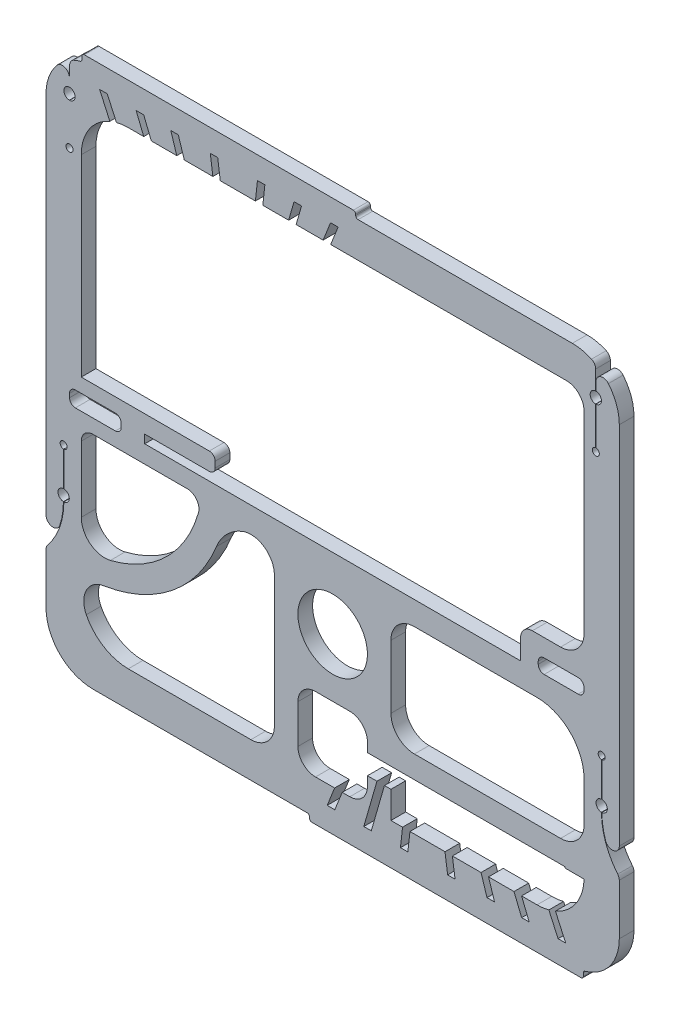
SolidWorks part; units mm, degrees
ref_plane "Front Plane" through (0, 0, 0) normal (0, 0, 1) x (1, 0, 0)
ref_plane "Top Plane" through (0, 0, 0) normal (0, 1, 0) x (1, 0, 0)
ref_plane "Right Plane" through (0, 0, 0) normal (1, 0, 0) x (0, 0, -1)
sketch "Sketch1" plane through (0, 0, 0) normal (0, 0, 1) x (1, 0, 0)
  line L0 (44.642, 21.8842) -> (44.642, 18.0742) construction
  line L1 (-10.1934, 21.8842) -> (51.7832, 21.8842)
  line L2 (-10.1934, 21.8842) -> (-10.1934, -36.406)
  line L3 (-10.1934, -36.406) -> (51.7832, -36.406)
  line L4 (51.7832, 21.8842) -> (51.7832, -36.406)
  line L5 (47.9732, -32.596) -> (-6.3834, -32.596)
  line L6 (47.9732, -32.596) -> (47.9732, 18.0742)
  line L7 (47.9732, 18.0742) -> (-6.3834, 18.0742)
  line L8 (-6.3834, -32.596) -> (-6.3834, 18.0742)
  line L9 (44.642, 19.9792) -> (-35.1587, 19.9792) construction
  line L10 (-6.3834, -31.0517) -> (-10.1934, -31.0517) construction
  line L11 (-8.2884, -31.0517) -> (-8.2884, 6.9585) construction
  line L12 (20.6521, 19.9792) -> (21.1982, 19.9792) construction
  line L14 (3.0779, -32.596) -> (3.0779, -36.406) construction
  line L15 (3.0779, -34.501) -> (37.3423, -34.501) construction
  line L16 (47.9732, -11.8991) -> (47.9732, 12.9942) construction
  line L17 (51.7832, 15.2205) -> (47.9732, 15.2205) construction
  line L18 (49.8782, 15.2205) -> (49.8782, -0.9437) construction
  line L20 (20.9378, -34.501) -> (20.3916, -34.501) construction
  line L21 (-6.3834, 8.0412) -> (-6.3834, -11.8991) construction
  dimension "D1" = 3.81
  dimension "D2" = 3.81
extrude "Boss-Extrude1" add sketch "Sketch1" along normal blind 1.5875
sketch "Sketch2" plane through (0, 0, 0) normal (0, 0, -1) x (-1, 0, 0)
  line L0 (-47.9732, -32.596) -> (-47.9732, 18.0742) construction
  line L1 (-34.8696, 3.2518) -> (6.3834, 3.2518) construction
  line L2 (-47.9732, 3.653) -> (-47.9732, 0.4065) construction
  line L3 (-37.4096, 0.7118) -> (6.3834, 0.7118) construction
  line L4 (6.3834, 3.2518) -> (6.3834, 0.7118) construction
  line L5 (6.3834, 18.0742) -> (6.3834, -32.596) construction
  line L8 (-47.9732, -13.182) -> (-9.1041, -13.182)
  line L9 (-47.9732, -13.182) -> (-47.9732, -10.642)
  line L10 (-47.9732, -10.642) -> (-6.771, -10.642)
  line L11 (1.357, -21.2563) -> (14.2432, -21.2563) construction
  line L12 (6.3834, -23.7963) -> (6.3834, -26.3363)
  line L13 (-47.9732, 13.8154) -> (-47.9732, 11.2754) construction
  line L14 (-41.1149, -10.642) -> (-0.4749, -10.642) construction
  line L15 (-40.2005, -1.1932) -> (-39.5655, -1.1932) construction
  arc A0 (-47.9732, 11.2754) -> (-37.4096, 0.7118) centre (-47.9732, 0.7118) cw construction
  arc A1 (-47.9732, 13.8154) -> (-34.8696, 3.2518) centre (-47.9732, 0.4065) cw construction
  arc A2 (6.3834, -23.7963) -> (-6.771, -10.642) centre (6.3834, -10.642) cw
  arc A3 (-9.1041, -13.182) -> (6.3834, -26.3363) centre (6.3834, -10.642) ccw
  circle A5 centre (1.357, -18.2591) radius 2.9972 construction
  line M5 (-47.9732, -32.596) -> (-47.9732, 18.0742)
  line M7 (6.3834, 18.0742) -> (6.3834, -32.596)
  dimension "D5" = 2.54
  dimension "D1" = 2.54
  dimension "D2" = 2.54
  dimension "D3" = 2.54
  dimension "D4" = 2.54
  dimension "D6" = 2.54
  dimension "D7" = 2.54
  dimension "D8" = 1.905
extrude "Boss-Extrude2" add sketch "Sketch2" against normal up to surface (1.5875 mm away) contours L8 A3 A2 L10 M7 M5 up to face at (20.7949, -7.2609, 1.5875)
sketch "Sketch3" plane through (0, 0, 0) normal (0, 0, -1) x (-1, 0, 0)
  line L0 (-47.9732, -7.1876) -> (-41.1149, -7.1876)
  line L1 (-47.9732, -10.642) -> (-47.9732, 18.0742) construction
  line L2 (-47.9732, -10.642) -> (-6.771, -10.642) construction
  line L3 (-41.1149, -7.1876) -> (-41.1149, -10.642)
  line L5 (-41.1149, -10.642) -> (-43.0199, -10.642)
  line L6 (-43.0199, -10.642) -> (-43.0199, -9.0926)
  line L7 (-43.0199, -9.0926) -> (-47.9732, -9.0926)
  line L8 (-47.9732, -9.0926) -> (-47.9732, -7.1876)
  line L19 (-0.4749, -9.7276) -> (-41.1149, -9.7276) construction
  line L21 (-41.1149, -9.7276) -> (-41.1149, -10.642) construction
  dimension "D1" = 1.905
  dimension "D2" = 1.905
  dimension "D3" = 2.54
extrude "Boss-Extrude3" add sketch "Sketch3" against normal up to surface (1.5875 mm away) up to face at (18.535, -2.3312, 1.5875)
fillet "Fillet1" radius 5.08 4 edges at (51.7832, -36.406, 0.7937) (-10.1934, -36.406, 0.7937) (-10.1934, 21.8842, 0.7937) (51.7832, 21.8842, 0.7937)
fillet "Fillet2" radius 5.08 6 edges at (9.1041, -13.182, 0.7937) (47.9732, -13.182, 0.7937) (47.9732, -32.596, 0.7937) (-6.3834, -32.596, 0.7937) (-6.3834, 18.0742, 0.7937) (6.771, -10.642, 0.7937)
fillet "Fillet3" radius 2.54 3 edges at (47.9732, -7.1876, 0.7938) (-6.3834, -26.3363, 0.7937) (-6.3834, -23.7963, 0.7937)
sketch "Sketch5" plane through (0, 0, 0) normal (0, 0, -1) x (-1, 0, 0)
  line L1 (-27.0941, -13.182) -> (-14.4957, -13.182)
  line L2 (-27.0941, -13.182) -> (-27.0941, -32.596)
  line L3 (-27.0941, -32.596) -> (-14.4957, -32.596)
  line L4 (-14.4957, -13.182) -> (-14.4957, -32.596)
  line L5 (1.3034, -32.596) -> (-42.8932, -32.596) construction
  line L6 (-24.5541, -18.2972) -> (-27.0941, -18.2972) construction
  line L7 (-42.8932, -13.182) -> (-12.943, -13.182) construction
  line L9 (-17.0357, -18.2972) -> (-14.4957, -18.2972) construction
  circle A1 centre (-20.7949, -18.2972) radius 3.7592 construction
  dimension "D1" = 2.54
extrude "Boss-Extrude4" add sketch "Sketch5" against normal up to surface (1.5875 mm away) up to face at (45.4966, -9.8673, 1.5875)
sketch "Sketch6" plane through (0, 0, 0) normal (0, 0, -1) x (-1, 0, 0)
  circle A0 centre (-20.7949, -18.2972) radius 3.7592 construction
  circle A1 centre (-20.7949, -18.2972) radius 3.7592
extrude "Cut-Extrude2" cut sketch "Sketch6" against normal up to surface (1.5875 mm away) up to face at (5.503, -23.566, 1.5875)
sketch "Sketch7" plane through (0, 0, 0) normal (0, 0, -1) x (-1, 0, 0)
  line L0 (-27.0941, -13.182) -> (-27.0941, -32.596) construction
  line L1 (-24.5541, -24.5964) -> (-17.0357, -24.5964)
  line L2 (-24.5541, -24.5964) -> (-24.5541, -32.596)
  line L3 (-24.5541, -32.596) -> (-17.0357, -32.596)
  line L4 (-17.0357, -24.5964) -> (-17.0357, -32.596)
  line L5 (-14.4957, -32.596) -> (-14.4957, -13.182) construction
  line L6 (1.3034, -32.596) -> (-14.4957, -32.596) construction
  line L7 (-20.7949, -22.0564) -> (-6.5424, -22.0564) construction
  line L8 (-20.7949, -22.0564) -> (-20.7949, -21.3452) construction
  circle A0 centre (-20.7949, -18.2972) radius 3.7592 construction
  dimension "D1" = 2.54
  dimension "D2" = 2.54
  dimension "D3" = 2.54
extrude "Cut-Extrude3" cut sketch "Sketch7" against normal up to surface (1.5875 mm away) up to face at (24.5541, -18.2972, 1.5875)
fillet "Fillet5" radius 1.905 4 edges at (24.5541, -32.596, 0.7937) (17.0357, -32.596, 0.7938) (17.0357, -24.5964, 0.7938) (24.5541, -24.5964, 0.7938)
sketch "Sketch8" plane through (0, 0, 0) normal (0, 0, -1) x (-1, 0, 0)
  line L0 (-47.9732, -27.516) -> (-47.9732, -18.262) construction
  line L1 (-47.9732, -25.103) -> (-27.0941, -25.103)
  line L2 (-47.9732, -25.103) -> (-47.9732, -27.643)
  line L3 (-47.9732, -27.643) -> (-27.0941, -27.643)
  line L4 (-27.0941, -25.103) -> (-27.0941, -27.643)
  line L5 (-27.0941, -13.182) -> (-27.0941, -32.596) construction
  line L6 (-45.7916, -27.643) -> (-20.3916, -27.643) construction
  dimension "D1" = 2.54
extrude "Boss-Extrude5" add sketch "Sketch8" against normal up to surface (1.5875 mm away) up to face at (20.7949, -28.5962, 1.5875)
fillet "Fillet6" radius 2.54 5 edges at (27.0941, -13.182, 0.7937) (14.4957, -13.182, 0.7937) (14.4957, -32.596, 0.7937) (27.0941, -25.103, 0.7937) (47.9732, -25.103, 0.7937)
sketch "Sketch4" plane through (0, 0, 0) normal (0, 0, -1) x (-1, 0, 0)
  line L32 (4.2018, 13.1212) -> (4.2018, 15.0262)
  line L33 (4.2018, 15.0262) -> (1.9539, 15.0262)
  line L34 (1.9539, 15.0262) -> (4.2018, 19.9792)
  line L35 (4.2018, 19.9792) -> (3.6556, 19.9792)
  line L36 (3.6556, 19.9792) -> (1.4078, 15.0262)
  line L37 (1.4078, 15.0262) -> (-1.7417, 15.0262)
  line L38 (-1.7417, 15.0262) -> (0.2648, 19.9792)
  line L39 (0.2648, 19.9792) -> (-0.2814, 19.9792)
  line L40 (-0.2814, 19.9792) -> (-2.2879, 15.0262)
  line L41 (-2.2879, 15.0262) -> (-5.0437, 15.0262)
  line L42 (-5.0437, 15.0262) -> (-3.469, 19.9792)
  line L43 (-3.469, 19.9792) -> (-4.0152, 19.9792)
  line L44 (-4.0152, 19.9792) -> (-5.5899, 15.0262)
  line L45 (-5.5899, 15.0262) -> (-8.3965, 15.0262)
  line L46 (-8.3965, 15.0262) -> (-7.7108, 19.9792)
  line L47 (-7.7108, 19.9792) -> (-8.257, 19.9792)
  line L48 (-8.257, 19.9792) -> (-8.9427, 15.0262)
  line L49 (-8.9427, 15.0262) -> (-12.2319, 15.0262)
  line L50 (-12.2319, 15.0262) -> (-12.7781, 19.9792)
  line L51 (-12.7781, 19.9792) -> (-13.3242, 19.9792)
  line L52 (-13.3242, 19.9792) -> (-12.7781, 15.0262)
  line L53 (-12.7781, 15.0262) -> (-15.2926, 15.0262)
  line L54 (-15.2926, 15.0262) -> (-16.7151, 19.9792)
  line L55 (-16.7151, 19.9792) -> (-17.2612, 19.9792)
  line L56 (-17.2612, 19.9792) -> (-15.8388, 15.0262)
  line L57 (-15.8388, 15.0262) -> (-18.6963, 15.0262)
  line L58 (-18.6963, 15.0262) -> (-20.6521, 19.9792)
  line L59 (-20.6521, 19.9792) -> (-21.1982, 19.9792)
  line L60 (-21.1982, 19.9792) -> (-19.2425, 15.0262)
  line L61 (-19.2425, 15.0262) -> (-21.1982, 15.0262)
  line L62 (-21.1982, 15.0262) -> (-21.1982, 13.1212)
  line L63 (-21.1982, 13.1212) -> (4.2018, 13.1212)
  line L64 (4.2018, 13.1212) -> (4.2018, 15.0262) construction
  line L65 (4.2018, 15.0262) -> (1.9539, 15.0262) construction
  line L66 (1.9539, 15.0262) -> (4.2018, 19.9792) construction
  line L67 (4.2018, 19.9792) -> (3.6556, 19.9792) construction
  line L68 (3.6556, 19.9792) -> (1.4078, 15.0262) construction
  line L69 (1.4078, 15.0262) -> (-1.7417, 15.0262) construction
  line L70 (-1.7417, 15.0262) -> (0.2648, 19.9792) construction
  line L71 (0.2648, 19.9792) -> (-0.2814, 19.9792) construction
  line L72 (-0.2814, 19.9792) -> (-2.2879, 15.0262) construction
  line L73 (-2.2879, 15.0262) -> (-5.0437, 15.0262) construction
  line L74 (-5.0437, 15.0262) -> (-3.469, 19.9792) construction
  line L75 (-3.469, 19.9792) -> (-4.0152, 19.9792) construction
  line L76 (-4.0152, 19.9792) -> (-5.5899, 15.0262) construction
  line L77 (-5.5899, 15.0262) -> (-8.3965, 15.0262) construction
  line L78 (-8.3965, 15.0262) -> (-7.7108, 19.9792) construction
  line L79 (-7.7108, 19.9792) -> (-8.257, 19.9792) construction
  line L80 (-8.257, 19.9792) -> (-8.9427, 15.0262) construction
  line L81 (-8.9427, 15.0262) -> (-12.2319, 15.0262) construction
  line L82 (-12.2319, 15.0262) -> (-12.7781, 19.9792) construction
  line L83 (-12.7781, 19.9792) -> (-13.3242, 19.9792) construction
  line L84 (-13.3242, 19.9792) -> (-12.7781, 15.0262) construction
  line L85 (-12.7781, 15.0262) -> (-15.2926, 15.0262) construction
  line L86 (-15.2926, 15.0262) -> (-16.7151, 19.9792) construction
  line L87 (-16.7151, 19.9792) -> (-17.2612, 19.9792) construction
  line L88 (-17.2612, 19.9792) -> (-15.8388, 15.0262) construction
  line L89 (-15.8388, 15.0262) -> (-18.6963, 15.0262) construction
  line L90 (-18.6963, 15.0262) -> (-20.6521, 19.9792) construction
  line L91 (-20.6521, 19.9792) -> (-21.1982, 19.9792) construction
  line L92 (-21.1982, 19.9792) -> (-19.2425, 15.0262) construction
  line L93 (-19.2425, 15.0262) -> (-21.1982, 15.0262) construction
  line L94 (-21.1982, 15.0262) -> (-21.1982, 13.1212) construction
  line L95 (-21.1982, 13.1212) -> (4.2018, 13.1212) construction
  line L96 (-45.7916, -27.643) -> (-45.7916, -29.548)
  line L97 (-45.7916, -29.548) -> (-43.5438, -29.548)
  line L98 (-43.5438, -29.548) -> (-45.7916, -34.501)
  line L99 (-45.7916, -34.501) -> (-45.2455, -34.501)
  line L100 (-45.2455, -34.501) -> (-42.9976, -29.548)
  line L101 (-42.9976, -29.548) -> (-39.8482, -29.548)
  line L102 (-39.8482, -29.548) -> (-41.8546, -34.501)
  line L103 (-41.8546, -34.501) -> (-41.3085, -34.501)
  line L104 (-41.3085, -34.501) -> (-39.302, -29.548)
  line L105 (-39.302, -29.548) -> (-36.5462, -29.548)
  line L106 (-36.5462, -29.548) -> (-38.1208, -34.501)
  line L107 (-38.1208, -34.501) -> (-37.5747, -34.501)
  line L108 (-37.5747, -34.501) -> (-36, -29.548)
  line L109 (-36, -29.548) -> (-33.1934, -29.548)
  line L110 (-33.1934, -29.548) -> (-33.879, -34.501)
  line L111 (-33.879, -34.501) -> (-33.3329, -34.501)
  line L112 (-33.3329, -34.501) -> (-32.6472, -29.548)
  line L113 (-32.6472, -29.548) -> (-29.358, -29.548)
  line L114 (-29.358, -29.548) -> (-28.8118, -34.501)
  line L115 (-28.8118, -34.501) -> (-28.2656, -34.501)
  line L116 (-28.2656, -34.501) -> (-28.8118, -29.548)
  line L117 (-28.8118, -29.548) -> (-26.2973, -29.548)
  line L118 (-26.2973, -29.548) -> (-24.8748, -34.501)
  line L119 (-24.8748, -34.501) -> (-24.3286, -34.501)
  line L120 (-24.3286, -34.501) -> (-25.7511, -29.548)
  line L121 (-25.7511, -29.548) -> (-22.8935, -29.548)
  line L122 (-22.8935, -29.548) -> (-20.9378, -34.501)
  line L123 (-20.9378, -34.501) -> (-20.3916, -34.501)
  line L124 (-20.3916, -34.501) -> (-22.3474, -29.548)
  line L125 (-22.3474, -29.548) -> (-20.3916, -29.548)
  line L126 (-20.3916, -29.548) -> (-20.3916, -27.643)
  line L127 (-20.3916, -27.643) -> (-45.7916, -27.643)
  line L128 (-45.7916, -27.643) -> (-45.7916, -29.548) construction
  line L129 (-45.7916, -29.548) -> (-43.5438, -29.548) construction
  line L130 (-43.5438, -29.548) -> (-45.7916, -34.501) construction
  line L131 (-45.7916, -34.501) -> (-45.2455, -34.501) construction
  line L132 (-45.2455, -34.501) -> (-42.9976, -29.548) construction
  line L133 (-42.9976, -29.548) -> (-39.8482, -29.548) construction
  line L134 (-39.8482, -29.548) -> (-41.8546, -34.501) construction
  line L135 (-41.8546, -34.501) -> (-41.3085, -34.501) construction
  line L136 (-41.3085, -34.501) -> (-39.302, -29.548) construction
  line L137 (-39.302, -29.548) -> (-36.5462, -29.548) construction
  line L138 (-36.5462, -29.548) -> (-38.1208, -34.501) construction
  line L139 (-38.1208, -34.501) -> (-37.5747, -34.501) construction
  line L140 (-37.5747, -34.501) -> (-36, -29.548) construction
  line L141 (-36, -29.548) -> (-33.1934, -29.548) construction
  line L142 (-33.1934, -29.548) -> (-33.879, -34.501) construction
  line L143 (-33.879, -34.501) -> (-33.3329, -34.501) construction
  line L144 (-33.3329, -34.501) -> (-32.6472, -29.548) construction
  line L145 (-32.6472, -29.548) -> (-29.358, -29.548) construction
  line L146 (-29.358, -29.548) -> (-28.8118, -34.501) construction
  line L147 (-28.8118, -34.501) -> (-28.2656, -34.501) construction
  line L148 (-28.2656, -34.501) -> (-28.8118, -29.548) construction
  line L149 (-28.8118, -29.548) -> (-26.2973, -29.548) construction
  line L150 (-26.2973, -29.548) -> (-24.8748, -34.501) construction
  line L151 (-24.8748, -34.501) -> (-24.3286, -34.501) construction
  line L152 (-24.3286, -34.501) -> (-25.7511, -29.548) construction
  line L153 (-25.7511, -29.548) -> (-22.8935, -29.548) construction
  line L154 (-22.8935, -29.548) -> (-20.9378, -34.501) construction
  line L155 (-20.9378, -34.501) -> (-20.3916, -34.501) construction
  line L156 (-20.3916, -34.501) -> (-22.3474, -29.548) construction
  line L157 (-22.3474, -29.548) -> (-20.3916, -29.548) construction
  line L158 (-20.3916, -29.548) -> (-20.3916, -27.643) construction
  line L159 (-20.3916, -27.643) -> (-45.7916, -27.643) construction
  line L263 (4.3288, 12.9942) -> (4.3288, 15.1532)
  line L264 (4.3288, 15.1532) -> (2.151, 15.1532)
  line L265 (2.151, 15.1532) -> (4.3989, 20.1062)
  line L266 (4.3989, 20.1062) -> (3.5738, 20.1062)
  line L267 (3.5738, 20.1062) -> (1.3259, 15.1532)
  line L268 (1.3259, 15.1532) -> (-1.5532, 15.1532)
  line L269 (-1.5532, 15.1532) -> (0.4532, 20.1062)
  line L270 (0.4532, 20.1062) -> (-0.367, 20.1062)
  line L271 (-0.367, 20.1062) -> (-2.3735, 15.1532)
  line L272 (-2.3735, 15.1532) -> (-4.8701, 15.1532)
  line L273 (-4.8701, 15.1532) -> (-3.2954, 20.1062)
  line L274 (-3.2954, 20.1062) -> (-4.1081, 20.1062)
  line L275 (-4.1081, 20.1062) -> (-5.6828, 15.1532)
  line L276 (-5.6828, 15.1532) -> (-8.2507, 15.1532)
  line L277 (-8.2507, 15.1532) -> (-7.565, 20.1062)
  line L278 (-7.565, 20.1062) -> (-8.3676, 20.1062)
  line L279 (-8.3676, 20.1062) -> (-9.0533, 15.1532)
  line L280 (-9.0533, 15.1532) -> (-12.1181, 15.1532)
  line L281 (-12.1181, 15.1532) -> (-12.6643, 20.1062)
  line L282 (-12.6643, 20.1062) -> (-13.466, 20.1062)
  line L283 (-13.466, 20.1062) -> (-12.9198, 15.1532)
  line L284 (-12.9198, 15.1532) -> (-15.1969, 15.1532)
  line L285 (-15.1969, 15.1532) -> (-16.6194, 20.1062)
  line L286 (-16.6194, 20.1062) -> (-17.4298, 20.1062)
  line L287 (-17.4298, 20.1062) -> (-16.0074, 15.1532)
  line L288 (-16.0074, 15.1532) -> (-18.6099, 15.1532)
  line L289 (-18.6099, 15.1532) -> (-20.5657, 20.1062)
  line L290 (-20.5657, 20.1062) -> (-21.3849, 20.1062)
  line L291 (-21.3849, 20.1062) -> (-19.4292, 15.1532)
  line L292 (-19.4292, 15.1532) -> (-21.3252, 15.1532)
  line L293 (-21.3252, 15.1532) -> (-21.3252, 12.9942)
  line L294 (-21.3252, 12.9942) -> (4.3288, 12.9942)
  line L295 (-45.9186, -27.516) -> (-45.9186, -29.675)
  line L296 (-45.9186, -29.675) -> (-43.7409, -29.675)
  line L297 (-43.7409, -29.675) -> (-45.9887, -34.628)
  line L298 (-45.9887, -34.628) -> (-45.1636, -34.628)
  line L299 (-45.1636, -34.628) -> (-42.9158, -29.675)
  line L300 (-42.9158, -29.675) -> (-40.0367, -29.675)
  line L301 (-40.0367, -29.675) -> (-42.0431, -34.628)
  line L302 (-42.0431, -34.628) -> (-41.2229, -34.628)
  line L303 (-41.2229, -34.628) -> (-39.2164, -29.675)
  line L304 (-39.2164, -29.675) -> (-36.7198, -29.675)
  line L305 (-36.7198, -29.675) -> (-38.2945, -34.628)
  line L306 (-38.2945, -34.628) -> (-37.4818, -34.628)
  line L307 (-37.4818, -34.628) -> (-35.9071, -29.675)
  line L308 (-35.9071, -29.675) -> (-33.3392, -29.675)
  line L309 (-33.3392, -29.675) -> (-34.0248, -34.628)
  line L310 (-34.0248, -34.628) -> (-33.2222, -34.628)
  line L311 (-33.2222, -34.628) -> (-32.5366, -29.675)
  line L312 (-32.5366, -29.675) -> (-29.4717, -29.675)
  line L313 (-29.4717, -29.675) -> (-28.9256, -34.628)
  line L314 (-28.9256, -34.628) -> (-28.1239, -34.628)
  line L315 (-28.1239, -34.628) -> (-28.67, -29.675)
  line L316 (-28.67, -29.675) -> (-26.3929, -29.675)
  line L317 (-26.3929, -29.675) -> (-24.9705, -34.628)
  line L318 (-24.9705, -34.628) -> (-24.16, -34.628)
  line L319 (-24.16, -34.628) -> (-25.5825, -29.675)
  line L320 (-25.5825, -29.675) -> (-22.9799, -29.675)
  line L321 (-22.9799, -29.675) -> (-21.0242, -34.628)
  line L322 (-21.0242, -34.628) -> (-20.205, -34.628)
  line L323 (-20.205, -34.628) -> (-22.1607, -29.675)
  line L324 (-22.1607, -29.675) -> (-20.2646, -29.675)
  line L325 (-20.2646, -29.675) -> (-20.2646, -27.516)
  line L326 (-20.2646, -27.516) -> (-45.9186, -27.516)
  dimension "D1" = 0
  dimension "D2" = 0
  dimension "D3" = 0.127
  dimension "D4" = 0.127
extrude "Cut-Extrude1" cut sketch "Sketch4" against normal up to surface (1.5875 mm away) up to face at (37.2819, -19.3942, 1.5875)
sketch "Sketch9" plane through (0, 0, 0) normal (0, 0, -1) x (-1, 0, 0)
  circle A0 centre (-49.2432, 18.0742) radius 0.6096 construction
  circle A1 centre (7.6534, 18.0742) radius 0.6096 construction
  circle A2 centre (8.2884, -19.8366) radius 0.6096 construction
  circle A3 centre (-49.8782, -19.8366) radius 0.6096 construction
  circle A4 centre (-49.2432, 18.0742) radius 0.6096
  circle A5 centre (7.6534, 18.0742) radius 0.6096
  circle A6 centre (8.2884, -19.8366) radius 0.6096
  circle A7 centre (-49.8782, -19.8366) radius 0.6096
extrude "Cut-Extrude4" cut sketch "Sketch9" against normal up to surface (1.5875 mm away) up to face at (31.4097, -31.792, 1.5875)
sketch "Sketch10" plane through (0, 0, 1.5875) normal (0, 0, 1) x (1, 0, 0)
  line L0 (-7.6407, 18.6837) -> (-7.6407, 20.7449) construction
  line L1 (-7.6407, 13.375) -> (-7.6407, 17.4647) construction
  line L2 (-7.6661, 17.4647) -> (-7.6661, 13.375) construction
  line L3 (-7.6661, 19.5715) -> (-7.6661, 18.6837) construction
  line L4 (-7.6407, 18.6837) -> (-7.6407, 20.7449)
  line L5 (-7.6407, 13.375) -> (-7.6407, 17.4647)
  line L6 (-7.6661, 17.4647) -> (-7.6661, 13.375)
  line L7 (-7.6661, 19.5715) -> (-7.6661, 18.6837)
  line L8 (49.2305, 18.6837) -> (49.2305, 20.7449) construction
  line L9 (49.2305, 13.375) -> (49.2305, 17.4647) construction
  line L10 (49.2559, 17.4647) -> (49.2559, 13.375) construction
  line L11 (49.2559, 19.5715) -> (49.2559, 18.6837) construction
  line L12 (49.2305, 18.6837) -> (49.2305, 20.7449)
  line L13 (49.2305, 13.375) -> (49.2305, 17.4647)
  line L14 (49.2559, 17.4647) -> (49.2559, 13.375)
  line L15 (49.2559, 19.5715) -> (49.2559, 18.6837)
  line L16 (49.8909, -15.5181) -> (49.8909, -19.2271) construction
  line L17 (49.8655, -15.5181) -> (49.8655, -19.2271) construction
  line L18 (49.8909, -15.5181) -> (49.8909, -19.2271)
  line L19 (49.8655, -15.5181) -> (49.8655, -19.2271)
  line L20 (-8.2757, -15.5181) -> (-8.2757, -19.2271) construction
  line L21 (-8.3011, -15.5181) -> (-8.3011, -19.2271) construction
  line L22 (-8.2757, -15.5181) -> (-8.2757, -19.2271)
  line L23 (-8.3011, -15.5181) -> (-8.3011, -19.2271)
  line L24 (51.7832, -31.326) -> (51.7832, 16.8042) construction
  line L25 (51.7832, -25.8445) -> (51.7832, -22.639)
  line L26 (-10.1934, 16.8042) -> (-10.1934, -31.326) construction
  line L27 (-10.1934, -22.639) -> (-10.1934, -25.8445)
  arc A1 (-7.1902, 21.4403) -> (-7.6407, 20.7449) centre (-6.8787, 20.7449) ccw construction
  arc A2 (-7.6661, 13.375) -> (-7.6407, 13.375) centre (-7.6534, 12.9942) ccw construction
  arc A3 (-7.6661, 19.5715) -> (-9.013, 20.0598) centre (-8.4281, 19.5715) ccw construction
  arc A4 (-5.1134, 21.8842) -> (-10.1934, 16.8042) centre (-5.1134, 16.8042) ccw construction
  arc A5 (-7.1902, 21.4403) -> (-7.6407, 20.7449) centre (-6.8787, 20.7449) ccw
  arc A6 (-7.6661, 13.375) -> (-7.6407, 13.375) centre (-7.6534, 12.9942) ccw
  arc A7 (-7.6661, 19.5715) -> (-9.013, 20.0598) centre (-8.4281, 19.5715) ccw
  arc A8 (-7.1902, 21.4403) -> (-9.013, 20.0598) centre (-5.1134, 16.8042) ccw
  circle A9 centre (-7.6534, 18.0742) radius 0.6096 construction
  arc A10 (-7.6407, 18.6837) -> (-7.6661, 18.6837) centre (-7.6534, 18.0742) ccw
  arc A11 (-7.6661, 17.4647) -> (-7.6407, 17.4647) centre (-7.6534, 18.0742) ccw
  arc A12 (49.2305, 20.7449) -> (48.7801, 21.4403) centre (48.4685, 20.7449) ccw construction
  arc A13 (49.2305, 13.375) -> (49.2559, 13.375) centre (49.2432, 12.9942) ccw construction
  arc A14 (50.6029, 20.0598) -> (49.2559, 19.5715) centre (50.0179, 19.5715) ccw construction
  arc A15 (49.2305, 20.7449) -> (48.7801, 21.4403) centre (48.4685, 20.7449) ccw
  arc A16 (49.2305, 13.375) -> (49.2559, 13.375) centre (49.2432, 12.9942) ccw
  arc A17 (50.6029, 20.0598) -> (49.2559, 19.5715) centre (50.0179, 19.5715) ccw
  arc A18 (49.8909, -15.5181) -> (49.8655, -15.5181) centre (49.8782, -15.1373) ccw construction
  arc A19 (49.9036, -20.4457) -> (50.2983, -22.8798) centre (57.6041, -20.4462) ccw construction
  arc A20 (49.8528, -20.4457) -> (51.6105, -25.3613) centre (57.6041, -20.4462) ccw construction
  arc A21 (50.2983, -22.8798) -> (51.7832, -22.639) centre (51.0212, -22.639) ccw construction
  arc A22 (51.7832, -25.8445) -> (51.6105, -25.3613) centre (51.0212, -25.8445) ccw construction
  arc A23 (49.8909, -15.5181) -> (49.8655, -15.5181) centre (49.8782, -15.1373) ccw
  arc A24 (49.9036, -20.4457) -> (50.2983, -22.8798) centre (57.6041, -20.4462) ccw
  arc A25 (49.8528, -20.4457) -> (51.6105, -25.3613) centre (57.6041, -20.4462) ccw
  arc A26 (50.2983, -22.8798) -> (51.7832, -22.639) centre (51.0212, -22.639) ccw
  arc A27 (51.7832, -25.8445) -> (51.6105, -25.3613) centre (51.0212, -25.8445) ccw
  arc A28 (-10.1934, -22.639) -> (-8.7084, -22.8798) centre (-9.4314, -22.639) ccw construction
  arc A29 (-10.0206, -25.3613) -> (-8.263, -20.4457) centre (-16.0142, -20.4462) ccw construction
  arc A30 (-8.7084, -22.8798) -> (-8.3138, -20.4457) centre (-16.0142, -20.4462) ccw construction
  arc A31 (-8.2757, -15.5181) -> (-8.3011, -15.5181) centre (-8.2884, -15.1373) ccw construction
  arc A32 (-10.1934, -22.639) -> (-8.7084, -22.8798) centre (-9.4314, -22.639) ccw
  arc A33 (-10.0206, -25.3613) -> (-8.263, -20.4457) centre (-16.0142, -20.4462) ccw
  arc A34 (-8.7084, -22.8798) -> (-8.3138, -20.4457) centre (-16.0142, -20.4462) ccw
  arc A35 (-8.2757, -15.5181) -> (-8.3011, -15.5181) centre (-8.2884, -15.1373) ccw
  arc A36 (51.7832, 16.8042) -> (46.7032, 21.8842) centre (46.7032, 16.8042) ccw construction
  arc A37 (50.6029, 20.0598) -> (48.7801, 21.4403) centre (46.7032, 16.8042) ccw
  circle A38 centre (49.2432, 18.0742) radius 0.6096 construction
  arc A39 (49.2559, 18.6837) -> (49.2305, 18.6837) centre (49.2432, 18.0742) ccw
  arc A40 (49.2305, 17.4647) -> (49.2559, 17.4647) centre (49.2432, 18.0742) ccw
  circle A41 centre (49.8782, -19.8366) radius 0.6096 construction
  arc A42 (49.8909, -19.2271) -> (49.8655, -19.2271) centre (49.8782, -19.8366) ccw
  arc A43 (49.8528, -20.4457) -> (49.9036, -20.4457) centre (49.8782, -19.8366) ccw
  circle A44 centre (-8.2884, -19.8366) radius 0.6096 construction
  arc A45 (-8.2757, -19.2271) -> (-8.3011, -19.2271) centre (-8.2884, -19.8366) ccw
  arc A46 (-8.3138, -20.4457) -> (-8.263, -20.4457) centre (-8.2884, -19.8366) ccw
  arc A47 (-10.0206, -25.3613) -> (-10.1934, -25.8445) centre (-9.4314, -25.8445) ccw construction
  arc A48 (-10.0206, -25.3613) -> (-10.1934, -25.8445) centre (-9.4314, -25.8445) ccw
extrude "Slots for carbon" cut sketch "Sketch10" against normal through all
fillet "Fillet7" radius 1.905 1 edges at (47.9732, 18.0742, 0.7937)
sketch "Sketch11" plane through (0, 0, 0) normal (0, 0, -1) x (-1, 0, 0)
  line L1 (-0.4749, -9.7276) -> (-0.4749, -10.642) construction
  line L2 (-7.1635, -12.547) -> (6.3834, -12.547)
  line L3 (6.3834, 12.9942) -> (6.3834, -20.9479) construction
  line L4 (6.3834, -12.547) -> (6.3834, -7.8226)
  line L5 (-0.4749, -10.642) -> (-11.129, -10.642)
  line L7 (-0.4749, -9.7276) -> (-0.4749, -10.642)
  line L8 (-0.4749, -9.7276) -> (-8.0949, -9.7276)
  line L9 (-8.0949, -9.7276) -> (-8.0949, -7.8226)
  line L10 (-8.0949, -7.8226) -> (6.3834, -7.8226)
  arc A0 (-6.2502, -14.3067) -> (-11.129, -10.642) centre (-11.129, -15.722) ccw construction
  arc A1 (-7.1635, -12.547) -> (-11.129, -10.642) centre (-11.129, -15.722) ccw
  dimension "D1" = 1.905
  dimension "D2" = 1.905
  dimension "D3" = 7.62
extrude "Boss-Extrude6" add sketch "Sketch11" against normal up to surface (1.5875 mm away) up to face at (20.7949, -2.3483, 1.5875)
fillet "Fillet8" radius 1.27 3 edges at (41.1149, -7.1876, 0.7938) (-6.3834, -12.547, 0.7937) (7.1635, -12.547, 0.7937)
sketch "Sketch12" plane through (0, 0, 0) normal (0, 0, -1) x (-1, 0, 0)
  line L0 (3.1233, -7.8226) -> (3.1233, -9.3466) construction
  line L1 (2.0651, -9.3466) -> (7.6534, -9.3466)
  line L2 (2.0651, -9.3466) -> (2.0651, -11.023)
  line L3 (2.0651, -11.023) -> (7.6534, -11.023)
  line L4 (7.6534, -9.3466) -> (7.6534, -11.023)
  line L5 (6.3834, -7.8226) -> (-8.0949, -7.8226) construction
  line L6 (2.0651, -10.1848) -> (-0.4749, -10.1848) construction
  line L7 (3.1233, -11.023) -> (3.1233, -12.547) construction
  line L8 (-5.0715, -12.547) -> (5.1134, -12.547) construction
  line L9 (-0.4749, -9.7276) -> (-0.4749, -10.642) construction
  line L10 (7.6534, -10.1848) -> (10.1934, -10.1848) construction
  line L11 (10.1934, 16.8042) -> (10.1934, -22.639) construction
  dimension "D1" = 1.524
  dimension "D2" = 2.54
extrude "Cut-Extrude5" cut sketch "Sketch12" against normal through all
fillet "Fillet9" radius 0.635 10 edges at (47.9732, -10.642, 0.7937) (47.9732, -9.0926, 0.7938) (43.0199, -9.0926, 0.7938) (43.0199, -10.642, 0.7938) (-7.6534, -11.023, 0.7937) (-7.6534, -9.3466, 0.7938) (-2.0651, -11.023, 0.7938) (-2.0651, -9.3466, 0.7938) (8.0949, -9.7276, 0.7937) (8.0949, -7.8226, 0.7937)
sketch "Sketch13" plane through (0, 0, 0) normal (0, 0, -1) x (-1, 0, 0)
  line L0 (-46.7032, 21.8842) -> (5.1134, 21.8842) construction
  line L1 (-23.2899, 21.8842) -> (5.1134, 21.8842)
  line L2 (-23.2899, 21.8842) -> (-23.2899, 22.5192)
  line L3 (-23.2899, 22.5192) -> (6.3039, 22.5192)
  line L4 (6.3039, 21.7427) -> (6.3039, 22.5192)
  line L5 (5.1134, -36.406) -> (-46.7032, -36.406) construction
  line L6 (-18.3, -36.406) -> (-46.7032, -36.406)
  line L7 (-18.3, -36.406) -> (-18.3, -37.041)
  line L8 (-18.3, -37.041) -> (-47.8937, -37.041)
  line L9 (-47.8937, -36.2645) -> (-47.8937, -37.041)
  arc A0 (7.1902, 21.4403) -> (5.1134, 21.8842) centre (5.1134, 16.8042) ccw construction
  arc A1 (6.3039, 21.7427) -> (5.1134, 21.8842) centre (5.1134, 16.8042) ccw
  arc A2 (-51.7832, -31.326) -> (-46.7032, -36.406) centre (-46.7032, -31.326) ccw construction
  arc A3 (-47.8937, -36.2645) -> (-46.7032, -36.406) centre (-46.7032, -31.326) ccw
  dimension "D1" = 0.635
  dimension "D2" = 1.905
  dimension "D3" = 1.905
  dimension "D4" = 0.635
  dimension "D5" = 1.905
  dimension "D6" = 1.905
extrude "Boss-Extrude7" add sketch "Sketch13" against normal up to surface (1.5875 mm away) up to face at (-4.8592, -10.1848, 1.5875)
fillet "Fillet10" radius 0.254 8 edges at (47.8937, -36.2645, 0.7937) (47.8937, -37.041, 0.7937) (18.3, -37.041, 0.7937) (18.3, -36.406, 0.7937) (23.2899, 21.8842, 0.7937) (23.2899, 22.5192, 0.7937) (-6.3039, 22.5192, 0.7937) (-6.3039, 21.7427, 0.7937)
